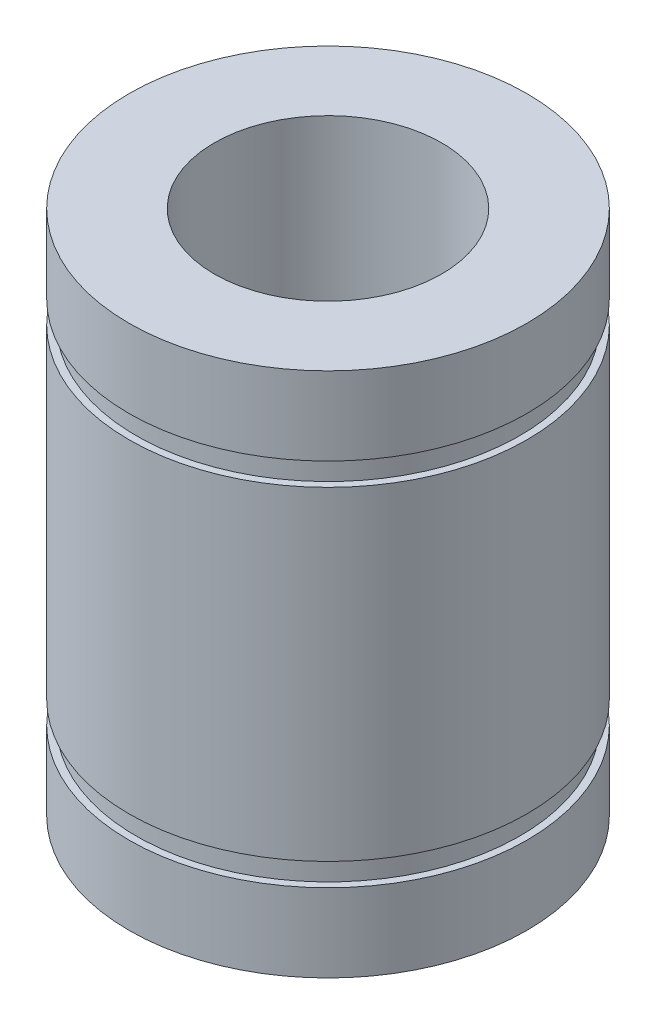
SolidWorks part; units mm, degrees
ref_plane "Спереди" through (0, 0, 0) normal (0, 0, 1) x (1, 0, 0)
ref_plane "Сверху" through (0, 0, 0) normal (0, 1, 0) x (1, 0, 0)
ref_plane "Справа" through (0, 0, 0) normal (1, 0, 0) x (0, 0, -1)
sketch "Эскиз2" plane through (0, 0, 0) normal (0, 0, 1) x (1, 0, 0)
  line L0 (13.5, 5.5) -> (14, 5.5)
  line L1 (0, 0) -> (14, 0)
  line L2 (0, 0) -> (0, 37)
  line L3 (0, 37) -> (14, 37)
  line L4 (14, 0) -> (14, 5.5)
  line L5 (13.5, 7.1) -> (14, 7.1)
  line L6 (13.5, 7.1) -> (13.5, 5.5)
  line L7 (14, 7.1) -> (14, 29.9)
  line L8 (13.5, 31.5) -> (14, 31.5)
  line L9 (13.5, 29.9) -> (14, 29.9)
  line L10 (13.5, 31.5) -> (13.5, 29.9)
  line L11 (14, 31.5) -> (14, 37)
  dimension "D1" = 37
  dimension "D2" = 14
  dimension "D3" = 5.5
  dimension "D4" = 1.6
  dimension "D5" = 0.5
  dimension "D6" = 5.5
  dimension "D7" = 1.6
  dimension "D8" = 0.5
revolve "Повернуть1" add sketch "Эскиз2" angle 360 about L2
sketch "Эскиз3" plane through (0, 37, 0) normal (0, 1, 0) x (1, 0, 0)
  circle A0 centre (0, 0) radius 8
  dimension "D1" = 16
extrude "Вырез-Вытянуть1" cut sketch "Эскиз3" against normal blind 37
